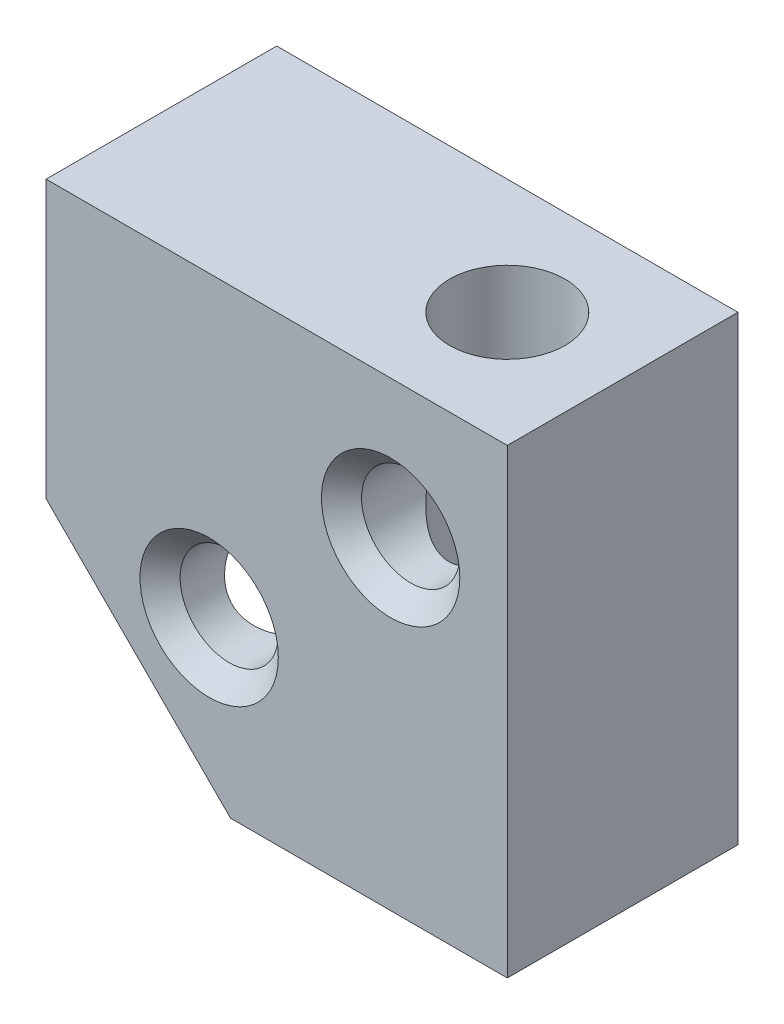
SolidWorks part; units mm, degrees
ref_plane "Front Plane" through (0, 0, 0) normal (0, 0, 1) x (1, 0, 0)
ref_plane "Top Plane" through (0, 0, 0) normal (0, 1, 0) x (1, 0, 0)
ref_plane "Right Plane" through (0, 0, 0) normal (1, 0, 0) x (0, 0, -1)
sketch "Sketch1" plane through (0, 0, 0) normal (0, 0, 1) x (1, 0, 0)
  line L0 (0, 0) -> (25.4, 0)
  line L1 (0, 0) -> (0, 25.4)
  line L2 (25.4, 0) -> (25.4, 25.4)
  line L3 (0, 25.4) -> (25.4, 25.4)
  dimension "D1" = 25.4
  dimension "D2" = 25.4
extrude "Boss-Extrude1" add sketch "Sketch1" along normal blind 12.7
chamfer "Chamfer1" distance 10.16 angle 45 1 edges at (0, 0, 6.35)
sketch "Sketch2" plane through (0, 25.4, 0) normal (0, 1, 0) x (1, 0, 0)
  line L0 (0, -6.35) -> (25.4, -6.35) construction
  line L1 (0, -12.7) -> (0, 0) construction
  line L2 (25.4, -12.7) -> (25.4, 0) construction
  circle A0 centre (19.05, -6.35) radius 3.175
  dimension "D2" = 6.35
  dimension "D1" = 19.05
extrude "Cut-Extrude1" cut sketch "Sketch2" against normal blind 25.4
sketch "Sketch3" plane through (5.08, 5.08, 0) normal (-0.7071, -0.7071, 0) x (0, 0, 1)
  line L0 (0, 0) -> (12.7, 0) construction
  line L1 (0, -7.1842) -> (0, 7.1842) construction
  line L2 (12.7, 7.1842) -> (12.7, -7.1842) construction
  line L3 (6.35, 7.1842) -> (6.35, -7.1842) construction
  line L4 (0, 7.1842) -> (12.7, 7.1842) construction
  line L5 (12.7, -7.1842) -> (0, -7.1842) construction
  circle A0 centre (6.35, 0) radius 3.175
  dimension "D1" = 6.35
extrude "Cut-Extrude2" cut sketch "Sketch3" against normal blind 10.16
hole_wizard "1/4-28 Tapped Hole1" positions "Sketch4" profile "Sketch5" tap size "1/4-28" standard "ANSI Inch"
sketch "Sketch4" plane through (0, 0, 12.7) normal (0, 0, 1) x (1, 0, 0)
  line L0 (0, 0) -> (8.9803, 8.9803) construction
  line L1 (0, 0) -> (18.9741, 0) construction
  line L2 (10.16, 0) -> (25.4, 0) construction
  line L3 (18.9741, 0) -> (18.9741, 17.78) construction
  point P0 (8.9803, 8.9803)
  point P2 (18.9741, 17.78)
  dimension "D1" = 17.78
  dimension "D2" = 18.9741
  dimension "D3" = 45
  dimension "D4" = 12.7
sketch "Sketch5" plane through (8.9803, 8.9803, 12.7) normal (1, 0, 0) x (0, -1, 0)
  line L0 (0, 0) -> (0, 17.1194)
  line L1 (0, 17.1194) -> (2.7051, 15.494)
  line L2 (2.7051, 15.494) -> (2.7051, 1.1049)
  line L3 (2.7051, 1.1049) -> (3.81, 0)
  line L5 (3.81, 0) -> (0, 0)
  line L6 (-2.7051, 1.1049) -> (-3.81, 0) construction
  line L10 (0, 17.1194) -> (-2.7051, 15.494) construction
  line L11 (0, -6.35) -> (0, 107.95) construction
  dimension "Tap Drill Dia." = 5.4102
  dimension "Tap Drill Depth" = 15.494
  dimension "Near C'Sink Dia." = 7.62
  dimension "Near C'Sink Angle" = 90
  dimension "Drill Angle" = 118
cosmetic thread "Hole Thread1" parameters "D1"=12.7, "D2"=6.35
cosmetic thread "Hole Thread2" parameters "D1"=12.7, "D2"=6.35
